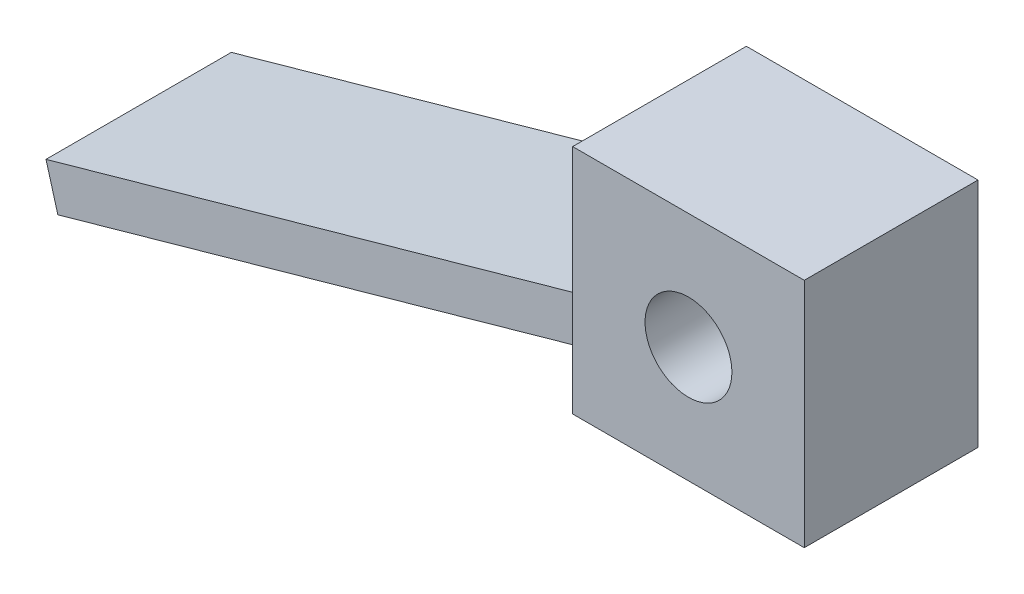
SolidWorks part; units mm, degrees
ref_plane "Alzado" through (0, 0, 0) normal (0, 0, 1) x (1, 0, 0)
ref_plane "Planta" through (0, 0, 0) normal (0, 1, 0) x (1, 0, 0)
ref_plane "Vista lateral" through (0, 0, 0) normal (1, 0, 0) x (0, 0, -1)
sketch "Croquis1" plane through (0, 0, 0) normal (0, 0, 1) x (1, 0, 0)
  line L0 (0, 0) -> (40, 0)
  line L1 (40, 0) -> (40, 40)
  line L2 (40, 40) -> (0, 40)
  line L3 (0, 40) -> (0, 0)
  dimension "D1" = 40
  dimension "D2" = 40
extrude "Saliente-Extruir1" add sketch "Croquis1" along normal blind 30
sketch "Croquis2" plane through (0, 0, 30) normal (0, 0, 1) x (1, 0, 0)
  circle A0 centre (20, 20) radius 7.5
  dimension "D1" = 15
extrude "Cortar-Extruir1" cut sketch "Croquis2" against normal blind 30
sketch "Croquis3" plane through (0, 0, 30) normal (0, 0, 1) x (1, 0, 0)
  line L0 (1.4951, 0) -> (9.4951, 0)
  line L1 (1.4951, 0) -> (-0.3742, -2.0203)
  line L2 (-0.3742, -2.0203) -> (-70.8243, -21.8444)
  line L3 (0, 0) -> (40, 0) construction
  line L4 (9.4951, 0) -> (-0.3742, -9.8693)
  line L5 (-0.3742, -9.8693) -> (-68.7777, -29.1175)
  line L6 (-68.7777, -29.1175) -> (-70.8243, -21.8444)
  dimension "D1" = 8
extrude "Saliente-Extruir2" add sketch "Croquis3" against normal blind 60
sketch "Croquis4" plane through (0, 0, 30) normal (0, 0, 1) x (1, 0, 0)
  line L0 (-70.8243, -21.8444) -> (-68.7777, -29.1175)
  line L1 (-68.7777, -29.1175) -> (-0.3742, -9.8693)
  line L2 (-0.3742, -9.8693) -> (9.4951, 0)
  line L3 (9.4951, 0) -> (1.4951, 0)
  line L4 (1.4951, 0) -> (-0.3742, -2.0203)
  line L5 (-0.3742, -2.0203) -> (-70.8243, -21.8444)
extrude "Cortar-Extruir2" cut sketch "Croquis4" against normal blind 28
sketch "Croquis5" plane through (2.5459, -9.0476, 0) normal (0.2709, -0.9626, 0) x (0.9626, 0.2709, 0)
  line L0 (-74.0936, 2) -> (-104.0936, 2)
  line L1 (-104.0936, 2) -> (-104.0936, -30)
  line L2 (-104.0936, -30) -> (-74.0936, -30)
  line L3 (-74.0936, -30) -> (-74.0936, 2)
  dimension "D1" = 30
extrude "Saliente-Extruir3" add sketch "Croquis5" against normal up to vertex (7.5555 mm away) up to point (-70.8243, -21.8444, 2)
sketch "Croquis6" plane through (2.5459, -9.0476, 0) normal (0.2709, -0.9626, 0) x (0.9626, 0.2709, 0)
  line L0 (-104.0936, 2) -> (-124.0936, 2)
  line L1 (-124.0936, 2) -> (-124.0936, -30)
  line L2 (-124.0936, -30) -> (-104.0936, -30)
  line L3 (-104.0936, -30) -> (-104.0936, 2)
  dimension "D1" = 20
extrude "Saliente-Extruir4" add sketch "Croquis6" against normal up to vertex (7.5555 mm away)
